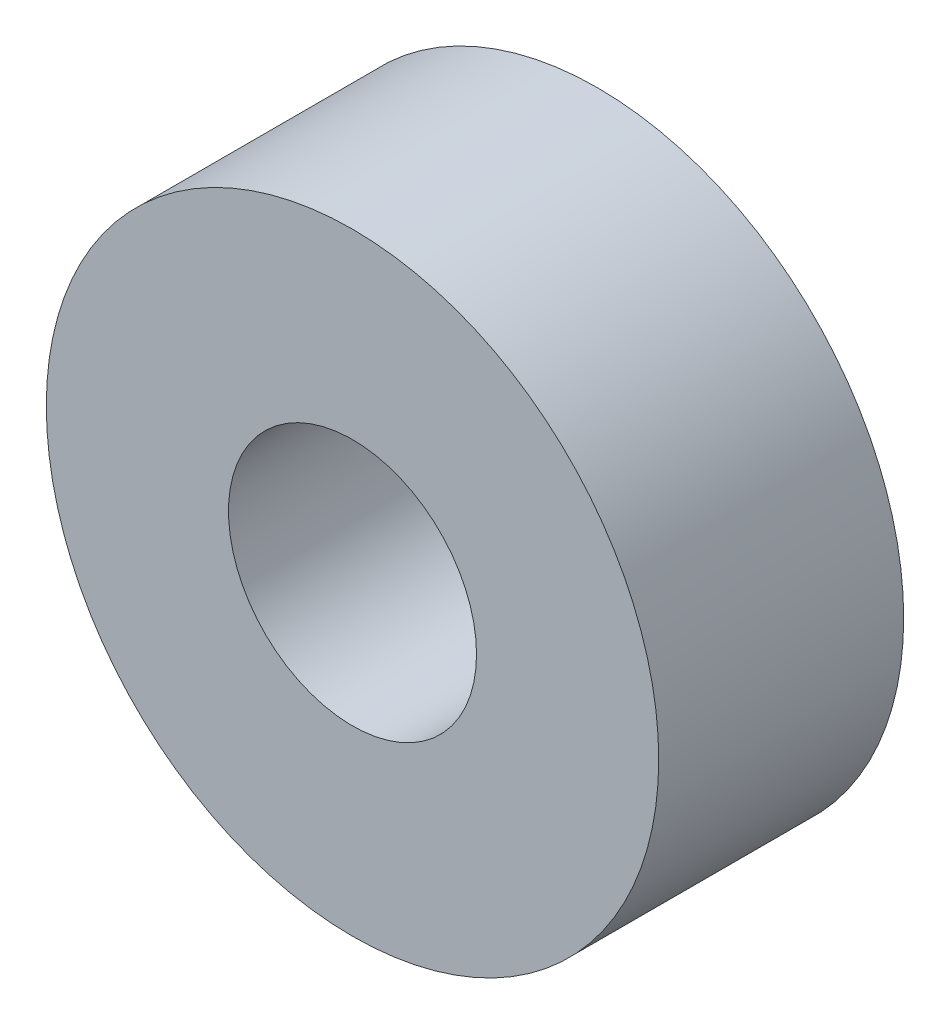
SolidWorks part; units mm, degrees
ref_plane "Front Plane" through (0, 0, 0) normal (0, 0, 1) x (1, 0, 0)
ref_plane "Top Plane" through (0, 0, 0) normal (0, 1, 0) x (1, 0, 0)
ref_plane "Right Plane" through (0, 0, 0) normal (1, 0, 0) x (0, 0, -1)
sketch "Sketch1" plane through (0, 0, 0) normal (0, 0, 1) x (1, 0, 0)
  circle A0 centre (0, 0) radius 4.05
  circle A1 centre (0, 0) radius 10
  dimension "D1" = 8.1
  dimension "D2" = 20
extrude "Boss-Extrude1" add sketch "Sketch1" along normal blind 8
